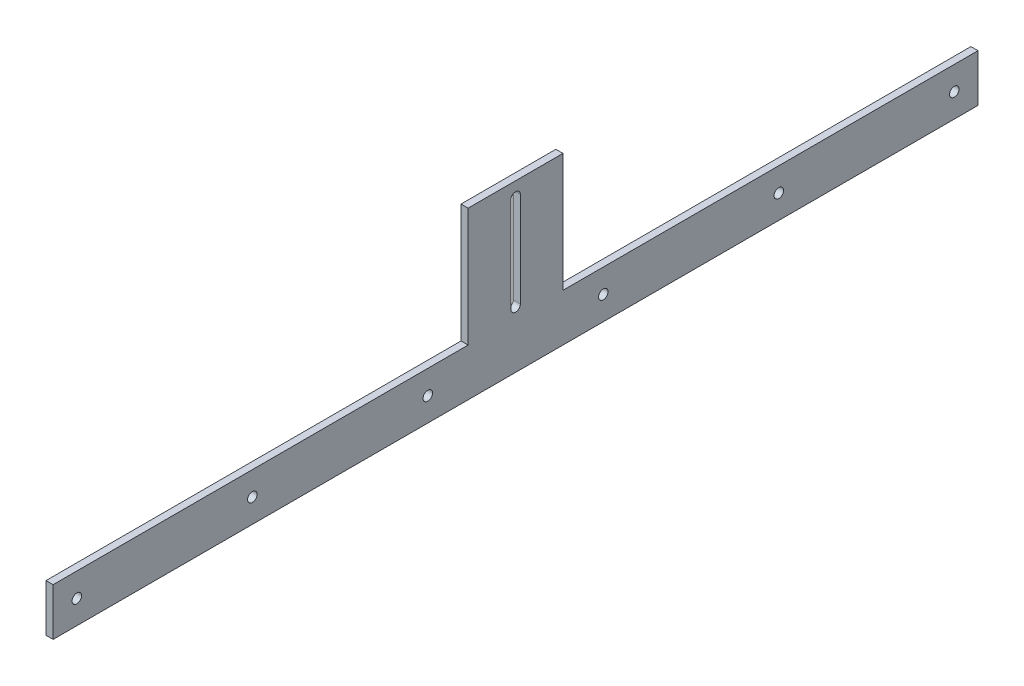
SolidWorks part; units mm, degrees
ref_plane "Ön Düzlem" through (0, 0, 0) normal (0, 0, 1) x (1, 0, 0)
ref_plane "Üst Düzlem" through (0, 0, 0) normal (0, 1, 0) x (1, 0, 0)
ref_plane "Sağ Düzlem" through (0, 0, 0) normal (1, 0, 0) x (0, 0, -1)
sketch "Çizim1" plane through (0, 0, 0) normal (1, 0, 0) x (0, 0, -1)
  line L0 (0, 10) -> (390, 10) construction
  line L1 (0, 0) -> (390, 0)
  line L2 (0, 0) -> (0, 20)
  line L3 (0, 20) -> (390, 20)
  line L4 (390, 0) -> (390, 20)
  circle A0 centre (10, 10) radius 2
  circle A1 centre (84, 10) radius 2
  circle A2 centre (158, 10) radius 2
  circle A3 centre (232, 10) radius 2
  circle A4 centre (306, 10) radius 2
  circle A5 centre (380, 10) radius 2
  dimension "D4" = 4
  dimension "D6" = 74
  dimension "D8" = 4
  dimension "D1" = 390
  dimension "D2" = 20
  dimension "D3" = 10
  dimension "D7" = 74
  dimension "D5" = 5
extrude "Yükseklik-Ekstrüzyon1" add sketch "Çizim1" along normal blind 3
sketch "Çizim2" plane through (3, 0, 0) normal (1, 0, 0) x (0, 0, -1)
  line L0 (195, 20) -> (195, 70) construction
  line L1 (390, 20) -> (0, 20) construction
  line L2 (195, 64) -> (195, 24) construction
  line L3 (175, 70) -> (215, 70)
  line L4 (175, 70) -> (175, 20)
  line L5 (175, 20) -> (215, 20)
  line L6 (215, 70) -> (215, 20)
  line L7 (197, 64) -> (197, 24)
  line L8 (193, 64) -> (193, 24)
  arc A0 (197, 64) -> (193, 64) centre (195, 64) ccw
  arc A1 (193, 24) -> (197, 24) centre (195, 24) ccw
  point P8 (195, 44)
  point P9 (195, 70)
  point P16 (0, 0)
  dimension "D1" = 50
  dimension "D2" = 40
  dimension "D3" = 4
  dimension "D4" = 40
  dimension "D5" = 6
extrude "Yükseklik-Ekstrüzyon2" add sketch "Çizim2" against normal up to vertex (3 mm away)
